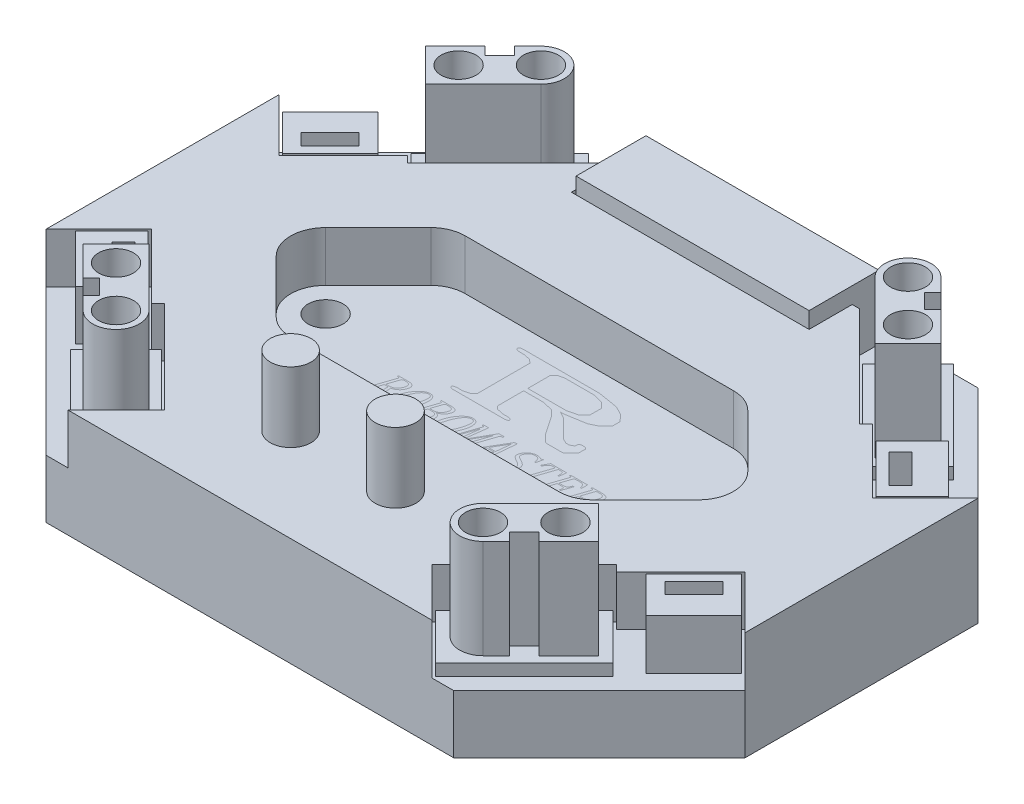
SolidWorks part; units mm, degrees
ref_plane "前视基准面" through (0, 0, 0) normal (0, 0, 1) x (1, 0, 0)
ref_plane "上视基准面" through (0, 0, 0) normal (0, 1, 0) x (1, 0, 0)
ref_plane "右视基准面" through (0, 0, 0) normal (1, 0, 0) x (0, 0, -1)
sketch "草图1" plane through (0, 0, 0) normal (0, 1, 0) x (1, 0, 0)
  line L0 (-30, 10) -> (-17.5, 22.5)
  line L1 (-17.5, -22.5) -> (17.5, -22.5)
  line L2 (-30, -10) -> (-30, 10)
  line L3 (-17.5, 22.5) -> (17.5, 22.5)
  line L4 (30, -10) -> (30, 10)
  line L5 (-30, -22.5) -> (30, 22.5) construction
  line L6 (-30, 22.5) -> (30, -22.5) construction
  line L7 (-30, -10) -> (-17.5, -22.5)
  line L8 (17.5, -22.5) -> (30, -10)
  line L9 (17.5, 22.5) -> (30, 10)
  line L10 (-16, 0) -> (16, 0) construction
  circle A0 centre (-16, 0) radius 1.5
  circle A1 centre (16, 0) radius 1.5
  point P0 (0, 0)
  dimension "D4" = 3
  dimension "D1" = 45
  dimension "D2" = 60
  dimension "D3" = 32
extrude "凸台-拉伸1" add sketch "草图1" along normal blind 5
sketch "草图2" plane through (0, 5, 0) normal (0, 1, 0) x (1, 0, 0)
  line L0 (-23.2825, 14.5962) -> (-19.3934, 10.7071)
  line L1 (-23.2825, 14.5962) -> (-15.6457, 22.2329)
  line L2 (-19.3934, 10.7071) -> (-11.7566, 18.3439)
  line L3 (-15.6457, 22.2329) -> (-11.7566, 18.3439)
  line L4 (-17.5, 22.5) -> (-30, 10) construction
  line L5 (0, 22.5) -> (0, -22.5) construction
  line L6 (17.5, 22.5) -> (-17.5, 22.5) construction
  line L7 (-17.5, -22.5) -> (17.5, -22.5) construction
  line L8 (-30, 0) -> (30, 0) construction
  line L9 (-30, 10) -> (-30, -10) construction
  line L10 (30, -10) -> (30, 10) construction
  line L11 (-15.7518, 18.2378) -> (-19.2873, 14.7023) construction
  line L12 (-19.4641, 18.4146) -> (-17.5196, 16.47) construction
  line L13 (19.4641, 18.4146) -> (17.5196, 16.47) construction
  line L14 (15.7518, 18.2378) -> (19.2873, 14.7023) construction
  line L15 (15.6457, 22.2329) -> (11.7566, 18.3439)
  line L16 (19.3934, 10.7071) -> (11.7566, 18.3439)
  line L17 (23.2825, 14.5962) -> (15.6457, 22.2329)
  line L18 (23.2825, 14.5962) -> (19.3934, 10.7071)
  line L19 (15.7518, -18.2378) -> (19.2873, -14.7023) construction
  line L20 (19.4641, -18.4146) -> (17.5196, -16.47) construction
  line L21 (-19.4641, -18.4146) -> (-17.5196, -16.47) construction
  line L22 (-15.7518, -18.2378) -> (-19.2873, -14.7023) construction
  line L23 (23.2825, -14.5962) -> (19.3934, -10.7071)
  line L24 (23.2825, -14.5962) -> (15.6457, -22.2329)
  line L25 (19.3934, -10.7071) -> (11.7566, -18.3439)
  line L26 (15.6457, -22.2329) -> (11.7566, -18.3439)
  line L27 (-15.6457, -22.2329) -> (-11.7566, -18.3439)
  line L28 (-19.3934, -10.7071) -> (-11.7566, -18.3439)
  line L29 (-23.2825, -14.5962) -> (-15.6457, -22.2329)
  line L30 (-23.2825, -14.5962) -> (-19.3934, -10.7071)
  circle A0 centre (-15.7518, 18.2378) radius 1.5
  circle A1 centre (-19.2873, 14.7023) radius 1.5
  circle A2 centre (19.2873, 14.7023) radius 1.5
  circle A3 centre (15.7518, 18.2378) radius 1.5
  circle A4 centre (15.7518, -18.2378) radius 1.5
  circle A5 centre (19.2873, -14.7023) radius 1.5
  circle A6 centre (-19.2873, -14.7023) radius 1.5
  circle A7 centre (-15.7518, -18.2378) radius 1.5
  point P23 (-13.7012, 20.2884)
  dimension "D5" = 3
  dimension "D1" = 10.8
  dimension "D2" = 5.5
  dimension "D3" = 1.5
  dimension "D4" = 8
  dimension "D6" = 5
extrude "凸台-拉伸2" add sketch "草图2" along normal blind 9.5
sketch "草图3" plane through (0, 14.5, 0) normal (0, 1, 0) x (1, 0, 0)
  line L0 (-14.3376, 16.8236) -> (-19.2873, 11.8738)
  line L1 (-19.2873, 11.8738) -> (-22.1158, 14.7023)
  line L2 (-22.1158, 14.7023) -> (-19.5702, 17.2478)
  line L3 (-19.5702, 17.2478) -> (-18.8631, 16.5407)
  line L4 (-18.8631, 16.5407) -> (-17.5903, 17.8135)
  line L5 (-17.5903, 17.8135) -> (-18.2974, 18.5206)
  line L6 (-18.2974, 18.5206) -> (-17.166, 19.652)
  line L7 (-19.2873, 14.7023) -> (-15.7518, 18.2378) construction
  line L8 (-17.5196, 16.47) -> (-18.2267, 17.1771) construction
  line L9 (0, 22.5) -> (0, -22.5) construction
  line L10 (17.5, 22.5) -> (-17.5, 22.5) construction
  line L11 (-17.5, -22.5) -> (17.5, -22.5) construction
  line L12 (-15.6457, 22.2329) -> (-23.2825, 14.5962)
  line L13 (-23.2825, 14.5962) -> (-19.3934, 10.7071)
  line L14 (-19.3934, 10.7071) -> (-11.7566, 18.3439)
  line L15 (-11.7566, 18.3439) -> (-15.6457, 22.2329)
  line L16 (-15.6457, 22.2329) -> (-23.2825, 14.5962)
  line L17 (-23.2825, 14.5962) -> (-19.3934, 10.7071)
  line L18 (-19.3934, 10.7071) -> (-11.7566, 18.3439)
  line L19 (-11.7566, 18.3439) -> (-15.6457, 22.2329)
  line L20 (-30, 0) -> (30, 0) construction
  line L21 (-30, 10) -> (-30, -10) construction
  line L22 (30, -10) -> (30, 10) construction
  line L23 (17.5196, 16.47) -> (18.2267, 17.1771) construction
  line L24 (19.2873, 14.7023) -> (15.7518, 18.2378) construction
  line L25 (11.7566, 18.3439) -> (15.6457, 22.2329)
  line L26 (19.3934, 10.7071) -> (11.7566, 18.3439)
  line L27 (23.2825, 14.5962) -> (19.3934, 10.7071)
  line L28 (15.6457, 22.2329) -> (23.2825, 14.5962)
  line L29 (18.2974, 18.5206) -> (17.166, 19.652)
  line L30 (17.5903, 17.8135) -> (18.2974, 18.5206)
  line L31 (18.8631, 16.5407) -> (17.5903, 17.8135)
  line L32 (19.5702, 17.2478) -> (18.8631, 16.5407)
  line L33 (22.1158, 14.7023) -> (19.5702, 17.2478)
  line L34 (19.2873, 11.8738) -> (22.1158, 14.7023)
  line L35 (14.3376, 16.8236) -> (19.2873, 11.8738)
  line L36 (19.2873, -14.7023) -> (15.7518, -18.2378) construction
  line L37 (17.5196, -16.47) -> (18.2267, -17.1771) construction
  line L38 (-17.5196, -16.47) -> (-18.2267, -17.1771) construction
  line L39 (-19.2873, -14.7023) -> (-15.7518, -18.2378) construction
  line L40 (14.3376, -16.8236) -> (19.2873, -11.8738)
  line L41 (19.2873, -11.8738) -> (22.1158, -14.7023)
  line L42 (22.1158, -14.7023) -> (19.5702, -17.2478)
  line L43 (19.5702, -17.2478) -> (18.8631, -16.5407)
  line L44 (18.8631, -16.5407) -> (17.5903, -17.8135)
  line L45 (17.5903, -17.8135) -> (18.2974, -18.5206)
  line L46 (18.2974, -18.5206) -> (17.166, -19.652)
  line L47 (15.6457, -22.2329) -> (23.2825, -14.5962)
  line L48 (23.2825, -14.5962) -> (19.3934, -10.7071)
  line L49 (19.3934, -10.7071) -> (11.7566, -18.3439)
  line L50 (11.7566, -18.3439) -> (15.6457, -22.2329)
  line L51 (-11.7566, -18.3439) -> (-15.6457, -22.2329)
  line L52 (-19.3934, -10.7071) -> (-11.7566, -18.3439)
  line L53 (-23.2825, -14.5962) -> (-19.3934, -10.7071)
  line L54 (-15.6457, -22.2329) -> (-23.2825, -14.5962)
  line L55 (-18.2974, -18.5206) -> (-17.166, -19.652)
  line L56 (-17.5903, -17.8135) -> (-18.2974, -18.5206)
  line L57 (-18.8631, -16.5407) -> (-17.5903, -17.8135)
  line L58 (-19.5702, -17.2478) -> (-18.8631, -16.5407)
  line L59 (-22.1158, -14.7023) -> (-19.5702, -17.2478)
  line L60 (-19.2873, -11.8738) -> (-22.1158, -14.7023)
  line L61 (-14.3376, -16.8236) -> (-19.2873, -11.8738)
  arc A0 (-14.3376, 16.8236) -> (-17.166, 19.652) centre (-15.7518, 18.2378) ccw
  circle A1 centre (-19.2873, 14.7023) radius 1.5 construction
  arc A2 (14.3376, 16.8236) -> (17.166, 19.652) centre (15.7518, 18.2378) cw
  arc A3 (14.3376, -16.8236) -> (17.166, -19.652) centre (15.7518, -18.2378) ccw
  arc A4 (-14.3376, -16.8236) -> (-17.166, -19.652) centre (-15.7518, -18.2378) cw
  dimension "D1" = 4
  dimension "D3" = 2
  dimension "D4" = 1
  dimension "D5" = 1.8
  dimension "D2" = 0
extrude "切除-拉伸1" cut sketch "草图3" against normal blind 8.5
sketch "草图4" plane through (0, 5, 0) normal (0, 1, 0) x (1, 0, 0)
  line L0 (-28.5858, 8.8686) -> (-24.4846, 12.9698)
  line L1 (-28.5858, 8.8686) -> (-25.4745, 5.7574)
  line L2 (-24.4846, 12.9698) -> (-21.3733, 9.8586)
  line L3 (-25.4745, 5.7574) -> (-21.3733, 9.8586)
  line L4 (-17.5, 22.5) -> (-30, 10) construction
  line L5 (-23.2825, 14.5962) -> (-19.3934, 10.7071) construction
  line L6 (-30, 0) -> (30, 0) construction
  line L7 (-30, 10) -> (-30, -10) construction
  line L8 (30, -10) -> (30, 10) construction
  line L9 (0, 22.5) -> (0, -22.5) construction
  line L10 (17.5, 22.5) -> (-17.5, 22.5) construction
  line L11 (-17.5, -22.5) -> (17.5, -22.5) construction
  line L12 (-26.217, 8.1262) -> (-23.7421, 10.601)
  line L13 (-26.217, 8.1262) -> (-25.227, 7.1362)
  line L14 (-23.7421, 10.601) -> (-22.7522, 9.6111)
  line L15 (-25.227, 7.1362) -> (-22.7522, 9.6111)
  line L16 (-23.9896, 8.3737) -> (-23.4239, 7.808) construction
  line L17 (23.9896, 8.3737) -> (23.4239, 7.808) construction
  line L18 (25.227, 7.1362) -> (22.7522, 9.6111)
  line L19 (23.7421, 10.601) -> (22.7522, 9.6111)
  line L20 (26.217, 8.1262) -> (25.227, 7.1362)
  line L21 (26.217, 8.1262) -> (23.7421, 10.601)
  line L22 (25.4745, 5.7574) -> (21.3733, 9.8586)
  line L23 (24.4846, 12.9698) -> (21.3733, 9.8586)
  line L24 (28.5858, 8.8686) -> (25.4745, 5.7574)
  line L25 (28.5858, 8.8686) -> (24.4846, 12.9698)
  line L26 (23.9896, -8.3737) -> (23.4239, -7.808) construction
  line L27 (-23.9896, -8.3737) -> (-23.4239, -7.808) construction
  line L28 (28.5858, -8.8686) -> (24.4846, -12.9698)
  line L29 (28.5858, -8.8686) -> (25.4745, -5.7574)
  line L30 (24.4846, -12.9698) -> (21.3733, -9.8586)
  line L31 (25.4745, -5.7574) -> (21.3733, -9.8586)
  line L32 (26.217, -8.1262) -> (23.7421, -10.601)
  line L33 (26.217, -8.1262) -> (25.227, -7.1362)
  line L34 (23.7421, -10.601) -> (22.7522, -9.6111)
  line L35 (25.227, -7.1362) -> (22.7522, -9.6111)
  line L36 (-25.227, -7.1362) -> (-22.7522, -9.6111)
  line L37 (-23.7421, -10.601) -> (-22.7522, -9.6111)
  line L38 (-26.217, -8.1262) -> (-25.227, -7.1362)
  line L39 (-26.217, -8.1262) -> (-23.7421, -10.601)
  line L40 (-25.4745, -5.7574) -> (-21.3733, -9.8586)
  line L41 (-24.4846, -12.9698) -> (-21.3733, -9.8586)
  line L42 (-28.5858, -8.8686) -> (-25.4745, -5.7574)
  line L43 (-28.5858, -8.8686) -> (-24.4846, -12.9698)
  dimension "D1" = 1.8
  dimension "D2" = 4.4
  dimension "D3" = 5.8
  dimension "D4" = 2
  dimension "D5" = 3.5
  dimension "D6" = 0.8
  dimension "D7" = 1.4
extrude "凸台-拉伸3" add sketch "草图4" along normal blind 4.3
sketch "草图6" plane through (0, 5, 0) normal (0, 1, 0) x (1, 0, 0)
  line L0 (0, 0) -> (0, 15.5) construction
  line L1 (-10, 21.5) -> (10, 21.5)
  line L2 (-10, 21.5) -> (-10, 15.5)
  line L3 (-10, 15.5) -> (10, 15.5)
  line L4 (10, 21.5) -> (10, 15.5)
  line L5 (17.5, 22.5) -> (-17.5, 22.5) construction
  dimension "D1" = 7
  dimension "D2" = 20
  dimension "D3" = 6
extrude "凸台-拉伸4" add sketch "草图6" along normal blind 5.5
sketch "草图5" plane through (0, 5, 0) normal (0, 1, 0) x (1, 0, 0)
  line L0 (-30, 10) -> (-30, -10)
  line L1 (-30, -10) -> (-25.4745, -5.4745)
  line L2 (-25.4745, -5.4745) -> (-19.9591, -10.9899)
  line L3 (-19.9591, -10.9899) -> (-19.3934, -10.4243)
  line L4 (-19.3934, -10.4243) -> (-11.4738, -18.3439)
  line L5 (-11.4738, -18.3439) -> (-15.6299, -22.5)
  line L6 (-17.5, -22.5) -> (17.5, -22.5) construction
  line L7 (-15.6299, -22.5) -> (15.6299, -22.5)
  line L8 (-30, 10) -> (-25.4745, 5.4745)
  line L9 (-25.4745, 5.4745) -> (-19.9591, 10.9899)
  line L10 (-19.9591, 10.9899) -> (-19.3934, 10.4243)
  line L11 (-19.3934, 10.4243) -> (-10.8177, 19)
  line L12 (-10.8177, 19) -> (-10.2, 19)
  line L13 (-10.2, 19) -> (-10.2, 15.3)
  line L14 (-10.2, 15.3) -> (10.2, 15.3)
  line L15 (0, 22.5) -> (0, -22.5) construction
  line L16 (17.5, 22.5) -> (-17.5, 22.5) construction
  line L17 (-30, 0) -> (30, 0) construction
  line L18 (-30, 10) -> (-30, -10) construction
  line L19 (-28.5858, 8.8686) -> (-25.4745, 5.7574) construction
  line L20 (-25.4745, 5.7574) -> (-21.3733, 9.8586) construction
  line L21 (-23.2825, 14.5962) -> (-19.3934, 10.7071) construction
  line L22 (-19.3934, 10.7071) -> (-11.7566, 18.3439) construction
  line L23 (-19.3934, -10.7071) -> (-23.2825, -14.5962) construction
  line L24 (-15.6457, -22.2329) -> (-11.7566, -18.3439) construction
  line L25 (-10, 15.5) -> (10, 15.5) construction
  line L26 (-10, 21.5) -> (-10, 15.5) construction
  line L27 (10.2, 19) -> (10.2, 15.3)
  line L28 (10.8177, 19) -> (10.2, 19)
  line L29 (19.3934, 10.4243) -> (10.8177, 19)
  line L30 (19.9591, 10.9899) -> (19.3934, 10.4243)
  line L31 (25.4745, 5.4745) -> (19.9591, 10.9899)
  line L32 (30, 10) -> (25.4745, 5.4745)
  line L33 (11.4738, -18.3439) -> (15.6299, -22.5)
  line L34 (19.3934, -10.4243) -> (11.4738, -18.3439)
  line L35 (19.9591, -10.9899) -> (19.3934, -10.4243)
  line L36 (25.4745, -5.4745) -> (19.9591, -10.9899)
  line L37 (30, -10) -> (25.4745, -5.4745)
  line L38 (30, 10) -> (30, -10)
  line L39 (-18.1213, 2.1213) -> (-13.6041, 6.6386)
  line L40 (-11.5244, 7.5) -> (11.5244, 7.5)
  line L41 (13.6041, 6.6386) -> (18.1213, 2.1213)
  line L42 (18.1213, -2.1213) -> (13.6041, -6.6386)
  line L43 (11.5244, -7.5) -> (-11.5244, -7.5)
  line L44 (-13.6041, -6.6386) -> (-18.1213, -2.1213)
  arc A0 (18.1213, 2.1213) -> (18.1213, -2.1213) centre (16, 0) cw
  arc A1 (-18.1213, 2.1213) -> (-18.1213, -2.1213) centre (-16, 0) ccw
  arc A2 (11.5244, 7.5) -> (13.6041, 6.6386) centre (11.5244, 4.5589) cw
  arc A3 (13.6041, -6.6386) -> (11.5244, -7.5) centre (11.5244, -4.5589) cw
  arc A4 (-11.5244, -7.5) -> (-13.6041, -6.6386) centre (-11.5244, -4.5589) cw
  arc A5 (-13.6041, 6.6386) -> (-11.5244, 7.5) centre (-11.5244, 4.5589) cw
  circle A6 centre (-16, 0) radius 1.5 construction
  point P46 (0, 0)
  point P47 (0, 15.3)
  point P63 (20.2426, 0)
  point P66 (-20.2426, 0)
  point P75 (11.07, 7.5)
  dimension "D11" = 3
  dimension "D12" = 2.9411
  dimension "D1" = 0.2
  dimension "D2" = 0.2
  dimension "D3" = 0.2
  dimension "D4" = 0.2
  dimension "D5" = 0.2
  dimension "D6" = 0.2
  dimension "D7" = 0.2
  dimension "D8" = 0.2
  dimension "D9" = 3.5
  dimension "D10" = 15
extrude "凸台-拉伸5" add sketch "草图5" along normal blind 4.3
sketch "草图7" plane through (0, 5, 0) normal (0, 1, 0) x (1, 0, 0)
  line L0 (-16, 0) -> (16, 0) construction
  line L1 (-15.0985, -4) -> (15.0985, -4) construction
  text T0 "R" font "SWRomnt" height 6
  text T1 "ROBOMASTER" font "宋体" height 2.5
  point P7 (0, -4)
  point P10 (15.0985, -4)
  dimension "D1" = 4
split line "分割线1"
sketch "草图8" plane through (0, 9.3, 0) normal (0, 1, 0) x (1, 0, 0)
  line L0 (-4.5, -14.5) -> (4.5, -14.5) construction
  line L1 (-15.6299, -22.5) -> (15.6299, -22.5) construction
  circle A0 centre (-4.5, -14.5) radius 1.75
  circle A1 centre (4.5, -14.5) radius 1.75
  point P4 (0, -14.5)
  dimension "D1" = 3.5
  dimension "D2" = 9
  dimension "D3" = 8
extrude "凸台-拉伸6" add sketch "草图8" along normal blind 6
